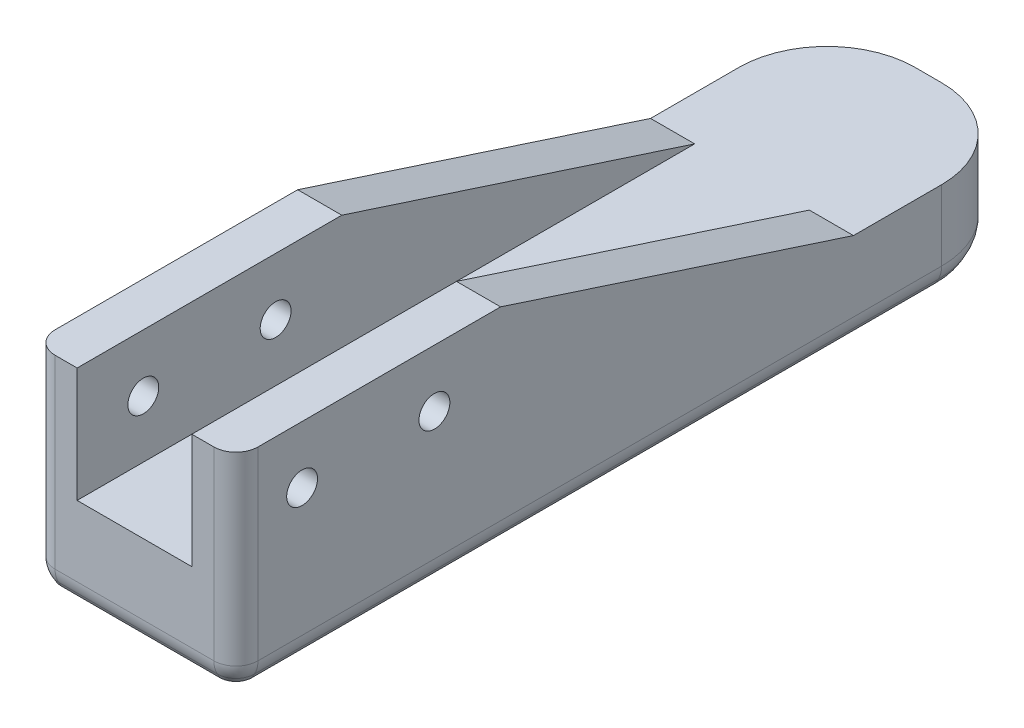
SolidWorks part; units mm, degrees
ref_plane "정면" through (0, 0, 0) normal (0, 0, 1) x (1, 0, 0)
ref_plane "윗면" through (0, 0, 0) normal (0, 1, 0) x (1, 0, 0)
ref_plane "우측면" through (0, 0, 0) normal (1, 0, 0) x (0, 0, -1)
sketch "스케치1" plane through (0, 0, 0) normal (0, 1, 0) x (1, 0, 0)
  line L1 (-11.5, -45) -> (11.5, -45)
  line L2 (-11.5, -45) -> (-11.5, 45)
  line L3 (-11.5, 45) -> (11.5, 45)
  line L4 (11.5, -45) -> (11.5, 45)
  line L5 (-11.5, -45) -> (11.5, 45) construction
  line L6 (-11.5, 45) -> (11.5, -45) construction
  point P0 (0, 0)
  dimension "D1" = 23
  dimension "D2" = 90
extrude "보스-돌출1" add sketch "스케치1" along normal mid plane 10
sketch "스케치2" plane through (0, -5, 0) normal (0, -1, 0) x (1, 0, 0)
  line L0 (0, -24.25) -> (0, 0) construction
  line L1 (0, 0) -> (0, 24.25) construction
  line L2 (-4.2317, 24.6443) -> (-6.472, 0.6031)
  line L3 (4.2317, 24.6443) -> (6.472, 0.6031)
  line L4 (6.472, -0.6031) -> (4.2317, -24.6443)
  line L5 (-6.472, -0.6031) -> (-4.2317, -24.6443)
  circle A0 centre (0, 0) radius 6.5
  circle A1 centre (0, 24.25) radius 4.25
  circle A2 centre (0, -24.25) radius 4.25
  point P7 (0, 28.5)
  point P8 (0, -28.5)
  dimension "D1" = 13
  dimension "D3" = 8.5
  dimension "D2" = 57
extrude "컷-돌출1" cut sketch "스케치2" against normal blind 3.5 contours A1 | A1 L2 A0 L3 | A0 | A2 L4 A0 L5 | A2
sketch "스케치4" plane through (0, 0, 0) normal (0, 0, 1) x (1, 0, 0)
  line L0 (-11.5, 5) -> (-11.5, 18)
  line L1 (-11.5, 18) -> (-6.5, 18)
  line L2 (-6.5, 18) -> (-6.5, 5)
  line L3 (-11.5, 5) -> (11.5, 5) construction
  line L4 (-6.5, 5) -> (-11.5, 5)
  line L5 (11.5, 5) -> (11.5, 18)
  line L6 (11.5, 18) -> (6.5, 18)
  line L7 (6.5, 18) -> (6.5, 5)
  line L8 (6.5, 5) -> (11.5, 5)
  line L9 (6.5, 18) -> (-6.5, 18)
  line L10 (0, 18) -> (0, 0) construction
  dimension "D1" = 13
  dimension "D2" = 13
extrude "보스-돌출3" add sketch "스케치4" along normal blind 30 from offset 15 contours L4 L2 L1 L0 | L7 L8 L5 L6
fillet "필렛2" radius 10 2 edges at (11.5, 0, -45) (-11.5, 0, -45)
sketch "스케치5" plane through (0, 0, 0) normal (1, 0, 0) x (0, 0, -1)
  line L0 (-15, 11.5) -> (-45, 11.5) construction
  line L1 (-15, 5) -> (-15, 18) construction
  line L2 (-45, 18) -> (-45, -5) construction
  line L3 (-37.5, 11.5) -> (-22.5, 11.5) construction
  circle A0 centre (-22.5, 11.5) radius 1.75
  circle A1 centre (-37.5, 11.5) radius 1.75
  point P12 (-30, 11.5)
  point P13 (-30, 11.5)
  dimension "D2" = 3.5
  dimension "D1" = 15
extrude "컷-돌출2" cut sketch "스케치5" against normal through all both and the other way through all
fillet "필렛3" radius 2.5 2 edges at (-11.5, 6.5, 45) (11.5, 6.5, 45)
sketch "스케치6" plane through (0, 0, 0) normal (1, 0, 0) x (0, 0, -1)
  line L0 (-15, 18) -> (25, 5)
  line L1 (-15, 5) -> (35, 5) construction
  line L2 (25, 5) -> (-15, 5)
  line L3 (-15, 5) -> (-15, 18)
  dimension "D1" = 40
extrude "보스-돌출4" add sketch "스케치6" along normal blind 5 from offset 6.5
mirror "대칭 복사1" about plane through (0, 0, 0) normal (1, 0, 0) of "보스-돌출4"
chamfer "모따기1" distance 1.2 angle 30 16 edges at (5.3518, -5, -12.6237) (6.5, -5, 0) (0, -5, -28.5) (5.3518, -5, 12.6237) (-5.3518, -5, -12.6237) (0, -5, 28.5) (-6.5, -5, 0) (-5.3518, -5, 12.6237) (-11.5, -5, 3.75) (-10.7678, -5, 44.2678) (-8.5711, -5, -42.0711) (0, -5, 45) (0, -5, -45) (10.7678, -5, 44.2678) (8.5711, -5, -42.0711) (11.5, -5, 3.75)
fillet "필렛4" radius 3 16 edges at (-10.7678, -3.8, 44.2678) (-11.5, -3.8, 3.75) (-8.5711, -3.8, -42.0711) (0, -3.8, -45) (8.5711, -3.8, -42.0711) (11.5, -3.8, 3.75) (10.7678, -3.8, 44.2678) (0, -3.8, 45) (0, -3.8, 28.5) (5.3518, -3.8, 12.6237) (6.5, -3.8, 0) (5.3518, -3.8, -12.6237) (0, -3.8, -28.5) (-5.3518, -3.8, -12.6237) (-6.5, -3.8, 0) (-5.3518, -3.8, 12.6237)
